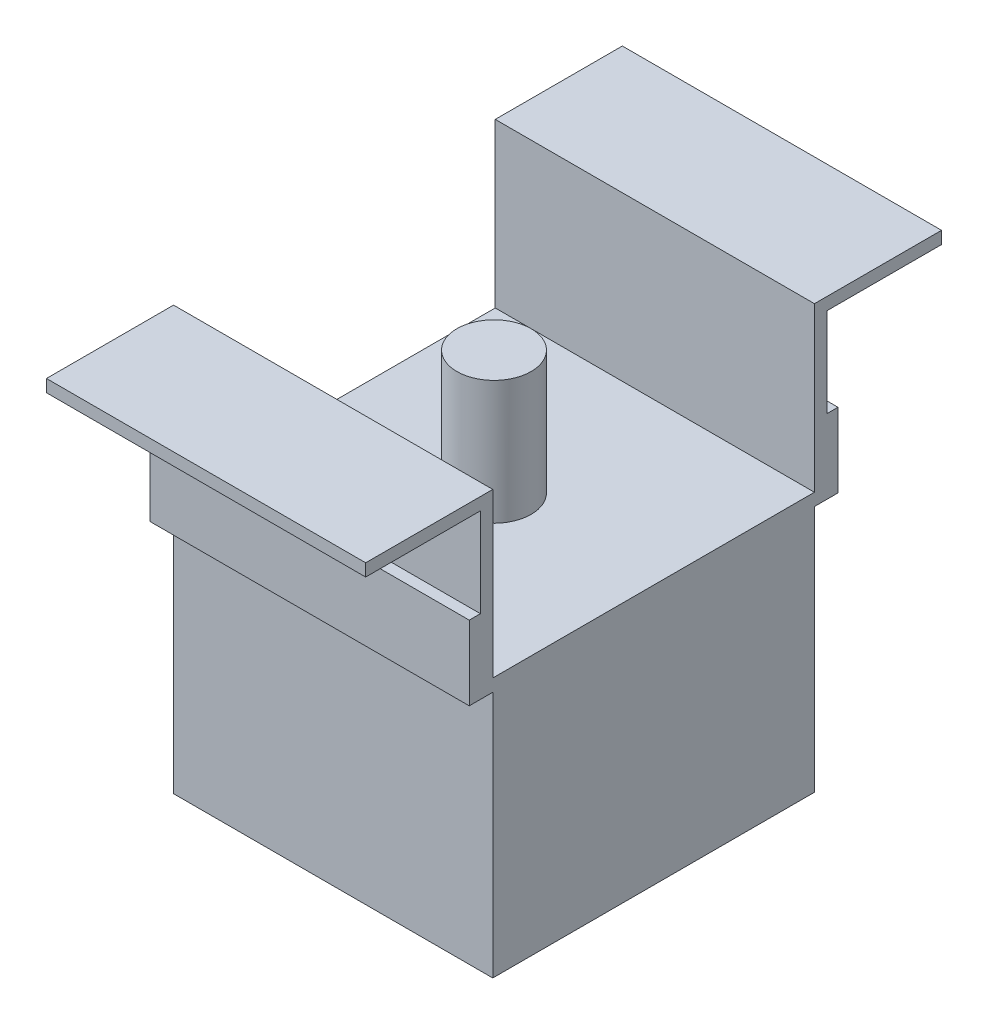
SolidWorks part; units mm, degrees
ref_plane "Płaszczyzna przednia" through (0, 0, 0) normal (0, 0, 1) x (1, 0, 0)
ref_plane "Płaszczyzna górna" through (0, 0, 0) normal (0, 1, 0) x (1, 0, 0)
ref_plane "Płaszczyzna prawa" through (0, 0, 0) normal (1, 0, 0) x (0, 0, -1)
sketch "Sketch1" plane through (0, 0, 0) normal (0, 1, 0) x (1, 0, 0)
  line L1 (0, 0) -> (12.9, 0)
  line L2 (0, 0) -> (0, 13)
  line L3 (0, 13) -> (12.9, 13)
  line L4 (12.9, 0) -> (12.9, 13)
  dimension "D1" = 13
  dimension "D2" = 12.9
extrude "Boss-Extrude1" add sketch "Sketch1" along normal blind 10
sketch "Sketch2" plane through (12.9, 0, 0) normal (1, 0, 0) x (0, 0, -1)
  line L0 (13, 10.5) -> (13, 17.1)
  line L1 (13, 17.1) -> (18.136, 17.1)
  line L2 (18.136, 17.1) -> (18.136, 16.6)
  line L3 (18.136, 16.6) -> (13.5, 16.6)
  line L4 (13.5, 16.6) -> (13.5, 10)
  line L6 (0, 0) -> (13, 0) construction
  line L8 (0, 10) -> (13, 10) construction
  line L9 (6.5, 10) -> (6.5, 10.5)
  line L10 (0, 10.5) -> (13, 10.5)
  line L11 (13.5, 10) -> (-0.5, 10)
  line L12 (-0.5, 16.6) -> (-0.5, 10)
  line L13 (-5.136, 16.6) -> (-0.5, 16.6)
  line L14 (-5.136, 17.1) -> (-5.136, 16.6)
  line L15 (0, 17.1) -> (-5.136, 17.1)
  line L16 (0, 10.5) -> (0, 17.1)
  line M12 (13, 10) -> (0, 10)
  dimension "D1" = 17.1
  dimension "D2" = 0.5
extrude "Boss-Extrude2" add sketch "Sketch2" against normal up to surface (12.9 mm away) contours L10 L16 L15 L14 L13 L12 L11 L9 M12 | L11 L4 L3 L2 L1 L0 L10 L9 M12 up to face at (0, 5, -6.5)
sketch "Sketch3" plane through (12.9, 0, 0) normal (1, 0, 0) x (0, 0, -1)
  line L0 (6.5, 10.5) -> (6.5, 6.4525) construction
  line L1 (-0.5, 10) -> (-0.95, 10)
  line L2 (-0.5, 10) -> (-0.5, 13)
  line L3 (-0.5, 13) -> (-0.95, 13)
  line L4 (-0.95, 10) -> (-0.95, 13)
  line L5 (0, 10.5) -> (13, 10.5) construction
  line L6 (13.5, 13) -> (13.95, 13)
  line L7 (13.95, 10) -> (13.95, 13)
  line L8 (13.5, 10) -> (13.95, 10)
  line L9 (13.5, 10) -> (13.5, 13)
  dimension "D1" = 3
  dimension "D2" = 14.9
extrude "Boss-Extrude3" add sketch "Sketch3" against normal up to surface (12.9 mm away) up to face at (0, 12.2375, -6.5)
sketch "Sketch4" plane through (0, 10.5, 0) normal (0, 1, 0) x (1, 0, 0)
  line L0 (0, 13) -> (12.9, 0) construction
  line L2 (12.9, 13) -> (0, 0) construction
  circle A0 centre (6.45, 6.5) radius 1.5
  dimension "D1" = 3
extrude "Boss-Extrude4" add sketch "Sketch4" along normal blind 5
